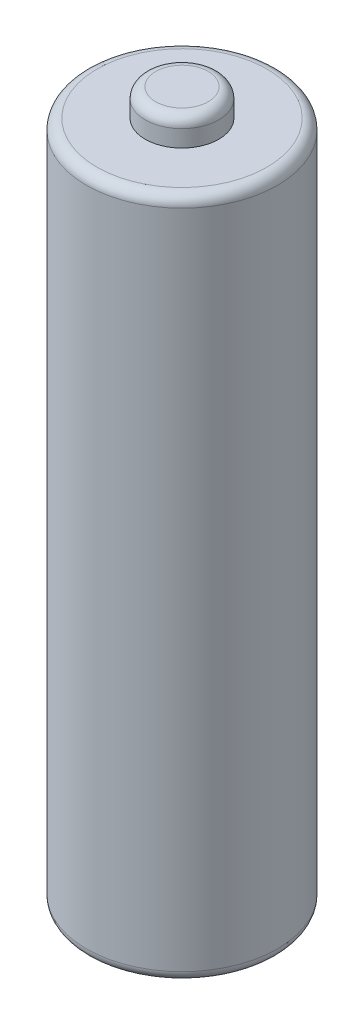
SolidWorks part; units mm, degrees
ref_plane "Alzado" through (0, 0, 0) normal (0, 0, 1) x (1, 0, 0)
ref_plane "Planta" through (0, 0, 0) normal (0, 1, 0) x (1, 0, 0)
ref_plane "Vista lateral" through (0, 0, 0) normal (1, 0, 0) x (0, 0, -1)
sketch "Croquis1" plane through (0, 0, 0) normal (0, 1, 0) x (1, 0, 0)
  circle A0 centre (0, 0) radius 9.1
  dimension "D1" = 18.2
extrude "Saliente-Extruir1" add sketch "Croquis1" along normal blind 65
sketch "Croquis2" plane through (0, 65, 0) normal (0, 1, 0) x (1, 0, 0)
  circle A0 centre (0, 0) radius 3.5
  dimension "D1" = 7
extrude "Saliente-Extruir2" add sketch "Croquis2" along normal blind 2.6
fillet "Redondeo1" radius 1 1 edges at (0, 67.6, 3.5)
fillet "Redondeo2" radius 1 2 edges at (0, 0, 9.1) (0, 65, 9.1)
